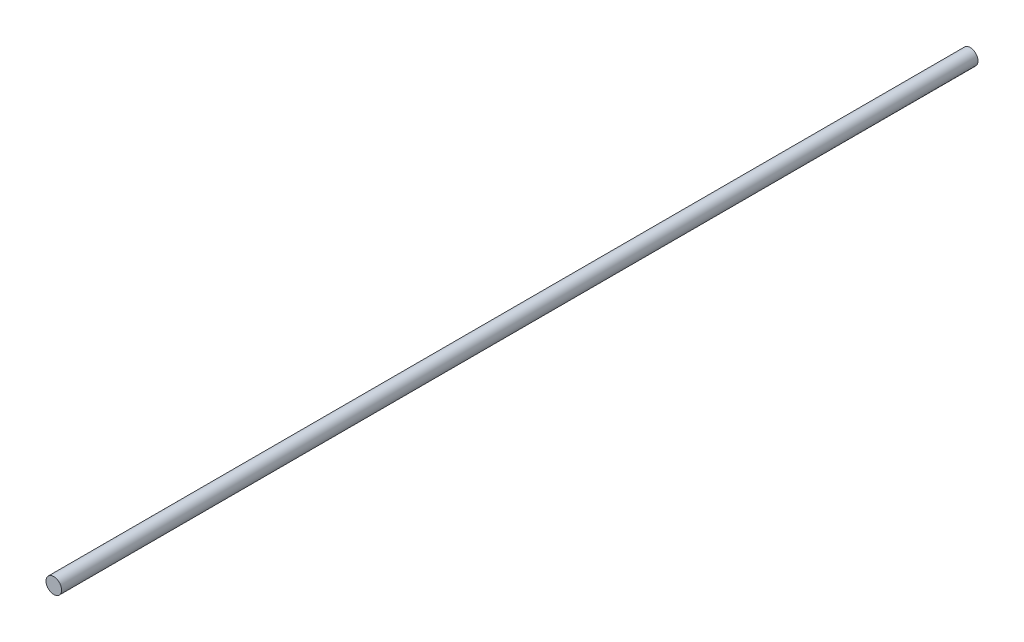
SolidWorks part; units mm, degrees
ref_plane "Front Plane" through (0, 0, 0) normal (0, 0, 1) x (1, 0, 0)
ref_plane "Top Plane" through (0, 0, 0) normal (0, 1, 0) x (1, 0, 0)
ref_plane "Right Plane" through (0, 0, 0) normal (1, 0, 0) x (0, 0, -1)
sketch "Sketch1" plane through (0, 0, 0) normal (0, 0, 1) x (1, 0, 0)
  circle A0 centre (0, 0) radius 2.5
  dimension "D1" = 5
extrude "Boss-Extrude1" add sketch "Sketch1" along normal blind 293.82
